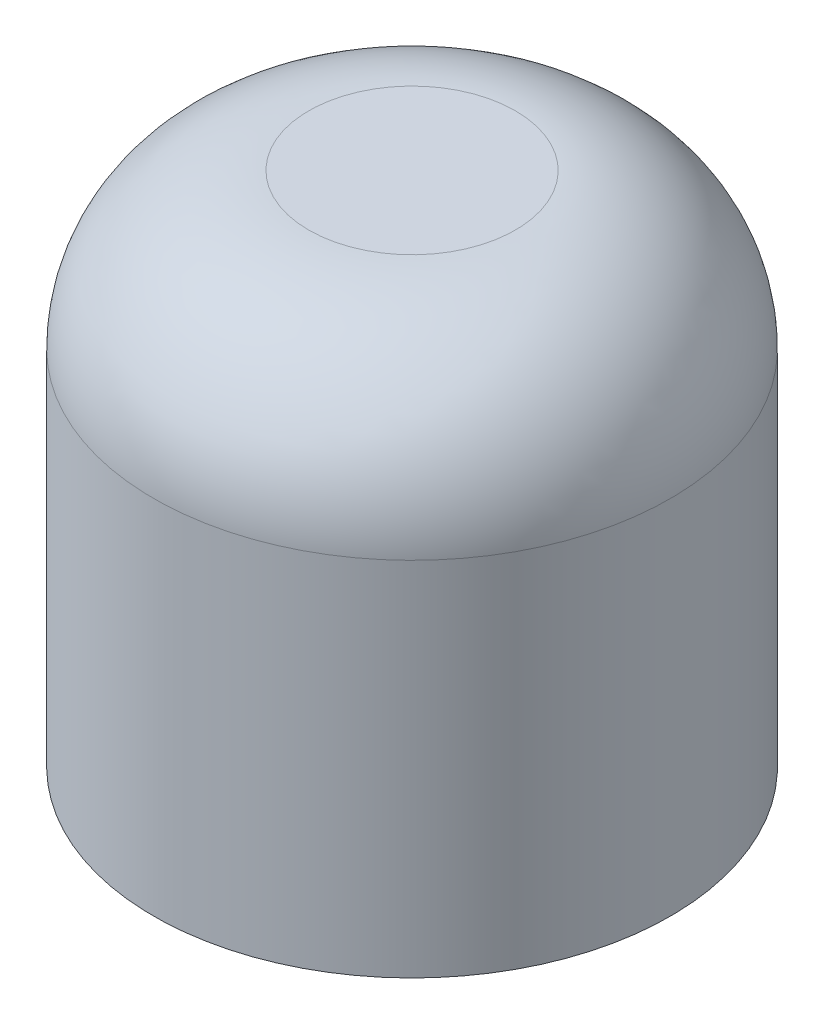
SolidWorks part; units mm, degrees
ref_plane "Front Plane" through (0, 0, 0) normal (0, 0, 1) x (1, 0, 0)
ref_plane "Top Plane" through (0, 0, 0) normal (0, 1, 0) x (1, 0, 0)
ref_plane "Right Plane" through (0, 0, 0) normal (1, 0, 0) x (0, 0, -1)
sketch "Sketch1" plane through (0, 0, 0) normal (0, 0, 1) x (1, 0, 0)
  line L0 (0, -6.5865) -> (0, 70.3202) construction
  line L2 (-6.35, 0) -> (-6.35, 12.7)
  line L5 (-6.35, 12.7) -> (0, 12.7)
  line L6 (-6.35, 0) -> (0, 0)
  line L7 (0, 0) -> (0, 12.7)
  dimension "D1" = 6.35
  dimension "D2" = 12.7
revolve "Revolve3" add sketch "Sketch1" angle 360 about L0
fillet "Fillet1" radius 3.81 1 edges at (0, 12.7, -6.35)
sketch "Sketch2" plane through (0, 0, 0) normal (0, -1, 0) x (-1, 0, 0)
  circle A0 centre (0, 0) radius 2.032
  dimension "D1" = 4.064
extrude "Cut-Extrude1" cut sketch "Sketch2" against normal blind 5.08
